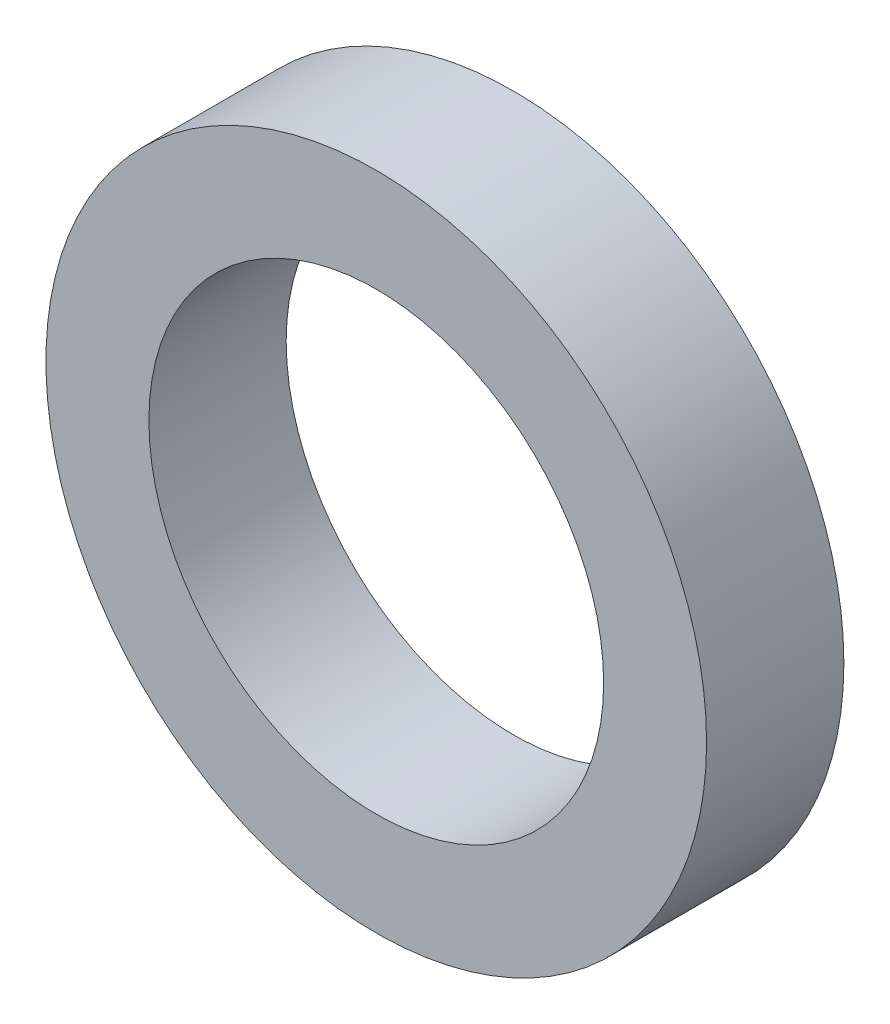
SolidWorks part; units mm, degrees
ref_plane "Front Plane" through (0, 0, 0) normal (0, 0, 1) x (1, 0, 0)
ref_plane "Top Plane" through (0, 0, 0) normal (0, 1, 0) x (1, 0, 0)
ref_plane "Right Plane" through (0, 0, 0) normal (1, 0, 0) x (0, 0, -1)
sketch "Sketch1" plane through (0, 0, 0) normal (0, 0, 1) x (1, 0, 0)
  circle A0 centre (0, 0) radius 2.65
  circle A1 centre (0, 0) radius 3.85
  dimension "D1" = 5.3
  dimension "D2" = 1.2
extrude "Boss-Extrude1" add sketch "Sketch1" along normal blind 1.6
